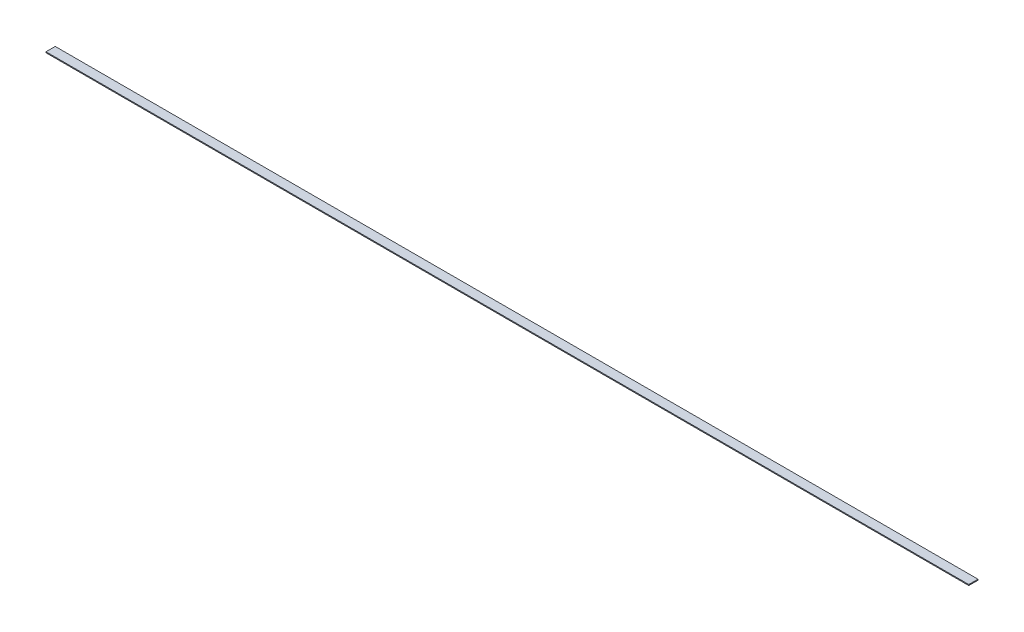
SolidWorks part; units mm, degrees
ref_plane "Front Plane" through (0, 0, 0) normal (0, 0, 1) x (1, 0, 0)
ref_plane "Top Plane" through (0, 0, 0) normal (0, 1, 0) x (1, 0, 0)
ref_plane "Right Plane" through (0, 0, 0) normal (1, 0, 0) x (0, 0, -1)
sketch "Sketch1" plane through (0, 0, 0) normal (0, 0, 1) x (1, 0, 0)
  line L1 (0, 0) -> (1000, 0)
  line L2 (0, 0) -> (0, 1)
  line L3 (0, 1) -> (1000, 1)
  line L4 (1000, 0) -> (1000, 1)
  dimension "D1" = 1
  dimension "D2" = 1000
extrude "Boss-Extrude1" add sketch "Sketch1" along normal blind 10
